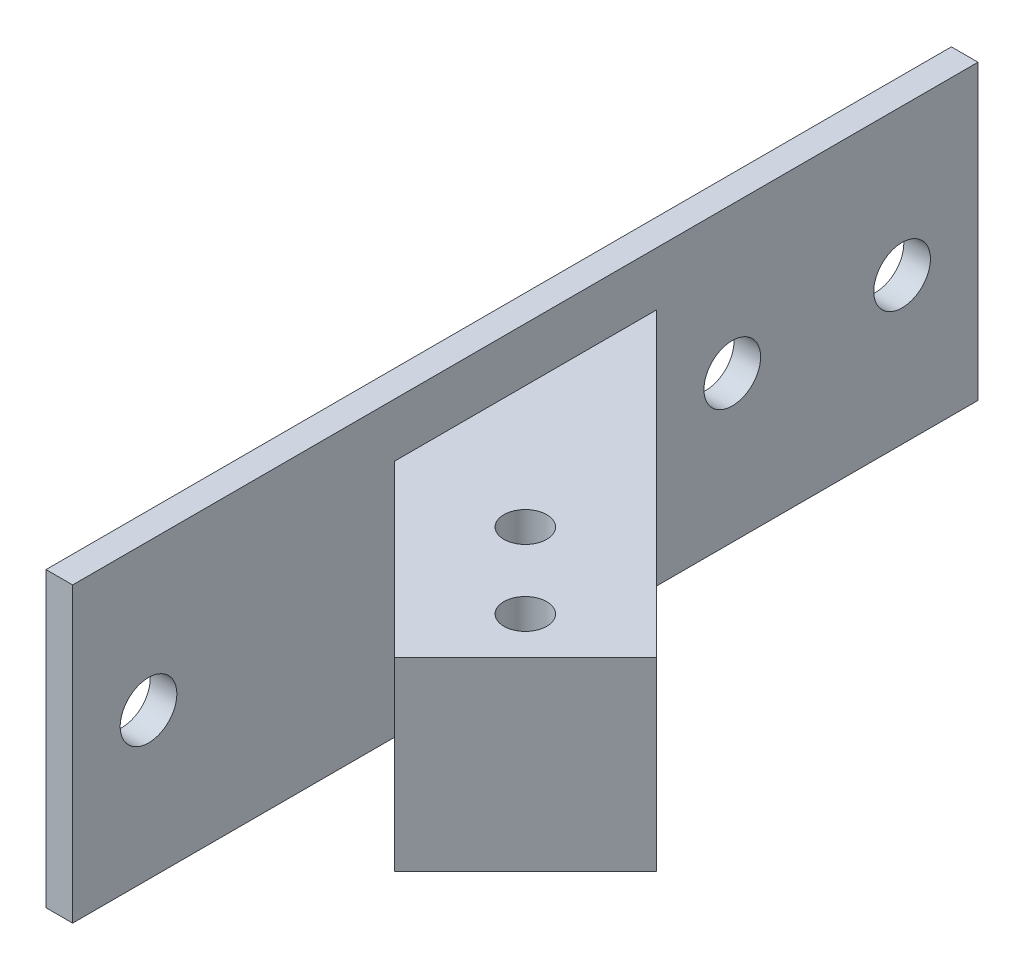
SolidWorks part; units mm, degrees
material "6061 Alloy"
ref_plane "Front" through (0, 0, 0) normal (0, 0, 1) x (1, 0, 0)
ref_plane "Top" through (0, 0, 0) normal (0, 1, 0) x (1, 0, 0)
ref_plane "Right" through (0, 0, 0) normal (1, 0, 0) x (0, 0, -1)
sketch "Sketch1" plane through (0, 0, 0) normal (1, 0, 0) x (0, 0, -1)
  line L1 (-53.975, 17.4625) -> (53.975, 17.4625)
  line L2 (-53.975, 17.4625) -> (-53.975, -17.4625)
  line L3 (-53.975, -17.4625) -> (53.975, -17.4625)
  line L4 (53.975, 17.4625) -> (53.975, -17.4625)
  line L5 (-53.975, 17.4625) -> (53.975, -17.4625) construction
  line L6 (-53.975, -17.4625) -> (53.975, 17.4625) construction
  point P0 (0, 0)
  dimension "D1" = 34.925
  dimension "D2" = 107.95
extrude "Boss-Extrude1" add sketch "Sketch1" along normal blind 3.175
sketch "Sketch3" plane through (0, 17.4625, 0) normal (0, 1, 0) x (1, 0, 0)
  line L0 (3.175, 0) -> (31.2383, -28.0633)
  line L1 (3.175, 53.975) -> (3.175, -53.975) construction
  line L2 (3.175, -20.2056) -> (21.1355, -38.1661)
  line L3 (3.175, 20.2056) -> (41.3411, -17.9605)
  line L4 (-3.9803, -13.0503) -> (21.1355, -38.1661) construction
  line L5 (16.2253, 7.1553) -> (41.3411, -17.9605) construction
  line L6 (6.1225, -2.9475) -> (31.2383, -28.0633) construction
  line L7 (21.1355, -38.1661) -> (31.2383, -28.0633)
  dimension "D1" = 14.2875
  dimension "D3" = 45
  dimension "D4" = 25.4
  dimension "D2" = 14.2875
sketch3d "3DSketch1"
  line L0 (3.175, 17.4625, 0) -> (31.2383, 17.4625, 28.0633) construction
sketch "Sketch4" plane through (29.6508, 0, 29.6508) normal (0.7071, 0, 0.7071) x (0.7071, 0, -0.7071)
  line L0 (2.2451, 17.4625) -> (2.2451, -17.4625) construction
  line L1 (-8.8039, -11.049) -> (13.2941, -11.049)
  line L2 (-8.8039, -11.049) -> (-8.8039, 11.049)
  line L3 (-8.8039, 11.049) -> (13.2941, 11.049)
  line L4 (13.2941, -11.049) -> (13.2941, 11.049)
  line L5 (-8.8039, -11.049) -> (13.2941, 11.049) construction
  line L6 (-8.8039, 11.049) -> (13.2941, -11.049) construction
  line L7 (40.4112, 17.4625) -> (-35.921, 17.4625) construction
  line L8 (-35.921, -17.4625) -> (40.4112, -17.4625) construction
  line L14 (-7.2164, 9.4615) -> (18.1836, -15.9385) construction
  line L15 (-10.4549, -12.7) -> (14.9451, 12.7) construction
  point P0 (2.2451, 0)
  point P12 (2.2451, 0)
  point P13 (2.2451, 0)
  dimension "D1" = 22.098
extrude "Boss-Extrude2" add sketch "Sketch4" against normal up to surface (28.6385 mm away)
sketch "Sketch5" plane through (3.175, 0, 0) normal (1, 0, 0) x (0, 0, -1)
  line L0 (15.6256, 0) -> (24.6751, 0) construction
  line L1 (-53.975, 17.4625) -> (-53.975, -17.4625) construction
  line L2 (-44.9256, 0) -> (-53.975, 0) construction
  line L3 (-53.975, 0) -> (-35.8761, 0) construction
  line L4 (-35.8761, 11.049) -> (-35.8761, -11.049) construction
  line L5 (15.6256, 11.049) -> (15.6256, -11.049) construction
  line L6 (24.6751, 0) -> (44.9256, 0) construction
  line L7 (44.9256, 0) -> (53.975, 0) construction
  line L8 (53.975, -17.4625) -> (53.975, 17.4625) construction
  circle A0 centre (-44.9256, 0) radius 3.3782
  circle A1 centre (24.6751, 0) radius 3.3782
  circle A2 centre (44.9256, 0) radius 3.3782
  point P17 (-44.9256, 0)
  dimension "D2" = 6.7564
extrude "Cut-Extrude1" cut sketch "Sketch5" against normal up to next
sketch "Sketch6" plane through (0, 11.049, 0) normal (0, 1, 0) x (1, 0, 0)
  line L0 (31.2383, -28.0633) -> (26.7482, -23.5732) construction
  line L1 (39.0511, -20.2505) -> (23.4255, -35.8761) construction
  line L2 (31.2383, -28.0633) -> (17.7679, -14.5929) construction
  line L3 (23.4255, -35.8761) -> (5.465, -17.9156) construction
  line L4 (3.175, -15.6256) -> (23.4255, -35.8761) construction
  circle A0 centre (26.7482, -23.5732) radius 3.3782
  circle A1 centre (17.7679, -14.5929) radius 3.3782
  dimension "D1" = 6.35
  dimension "D2" = 6.7564
  dimension "D3" = 25.4
  dimension "D4" = 19.05
hole_wizard "1/4-20 Tapped Hole1" positions "Sketch7" profile "Sketch8" tap size "1/4-20" standard "ANSI Inch" end condition through all
sketch "Sketch7" plane through (0, 11.049, 0) normal (0, 1, 0) x (1, 0, 0)
  point P0 (17.7679, -14.5929)
  point P3 (26.7482, -23.5732)
sketch "Sketch8" plane through (17.7679, 11.049, 14.5929) normal (1, 0, 0) x (0, 0, 1)
  line L0 (0, 0) -> (0, 28.5115)
  line L1 (0, 28.5115) -> (2.5527, 28.5115)
  line L2 (2.5527, 28.5115) -> (2.5527, 0)
  line L5 (2.5527, 0) -> (0, 0)
  line L11 (0, -6.35) -> (0, 107.95) construction
  dimension "Thru Tap Drill Dia." = 5.1054
  dimension "Thru Tap Drill Depth" = 28.5115
